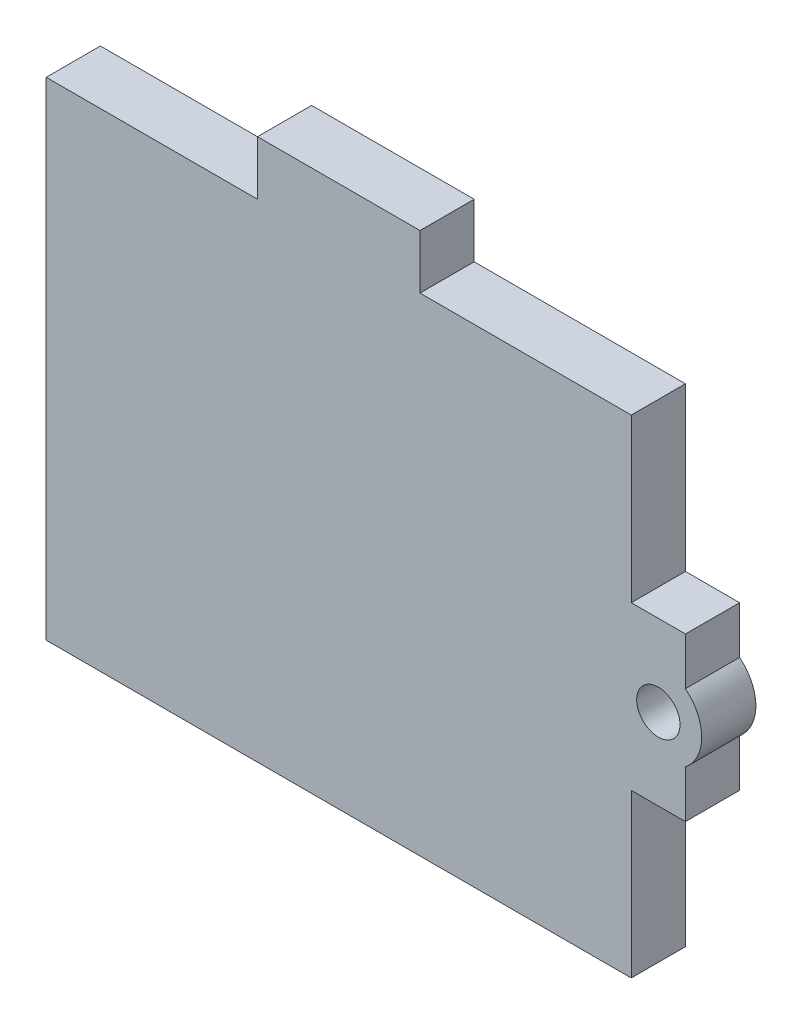
SolidWorks part; units mm, degrees
ref_plane "Front Plane" through (0, 0, 0) normal (0, 0, 1) x (1, 0, 0)
ref_plane "Top Plane" through (0, 0, 0) normal (0, 1, 0) x (1, 0, 0)
ref_plane "Right Plane" through (0, 0, 0) normal (1, 0, 0) x (0, 0, -1)
sketch "Sketch1" plane through (0, 0, 0) normal (0, 0, 1) x (1, 0, 0)
  line L1 (-27, 22.5) -> (27, 22.5)
  line L2 (-27, 22.5) -> (-27, -22.5)
  line L3 (-27, -22.5) -> (27, -22.5)
  line L4 (27, 22.5) -> (27, -22.5)
  dimension "D1" = 54
  dimension "D2" = 45
  dimension "D3" = 27
  dimension "D4" = 22.5
extrude "Boss-Extrude1" add sketch "Sketch1" along normal blind 5
sketch "Sketch3" plane through (0, 0, 5) normal (0, 0, 1) x (1, 0, 0)
  line L0 (27, -22.5) -> (27, 22.5) construction
  line L1 (27, 7.5) -> (32, 7.5)
  line L2 (27, 7.5) -> (27, -7.5)
  line L3 (27, -7.5) -> (32, -7.5)
  line L4 (32, 7.5) -> (32, -7.5)
  line L5 (32, 22.5) -> (32, 7.5) construction
  line L6 (27, 22.5) -> (-27, 22.5) construction
  line L7 (85, 27.5) -> (7.5, 27.5) construction
  line L8 (-7.5, 22.5) -> (7.5, 22.5)
  line L9 (-7.5, 22.5) -> (-7.5, 27.5)
  line L10 (-7.5, 27.5) -> (7.5, 27.5)
  line L11 (7.5, 22.5) -> (7.5, 27.5)
  line L13 (-27, 22.5) -> (-27, -22.5) construction
  dimension "D1" = 15
  dimension "D2" = 15
  dimension "D3" = 19.5
  dimension "D4" = 15
extrude "Boss-Extrude2" add sketch "Sketch3" against normal blind 5
sketch "Sketch4" plane through (0, 0, 5) normal (0, 0, 1) x (1, 0, 0)
  line L0 (32, -7.5) -> (32, 7.5) construction
  line L1 (27, -7.5) -> (32, -7.5) construction
  circle A0 centre (29.5, 0) radius 2
  dimension "D1" = 4
  dimension "D2" = 2.5
  dimension "D3" = 7.5
extrude "Cut-Extrude1" cut sketch "Sketch4" against normal blind 5
sketch "Sketch5" plane through (0, 0, 5) normal (0, 0, 1) x (1, 0, 0)
  circle A0 centre (29.5, 0) radius 2
  circle A1 centre (29.5, 0) radius 4
  dimension "D1" = 8
extrude "Boss-Extrude3" add sketch "Sketch5" against normal blind 5
